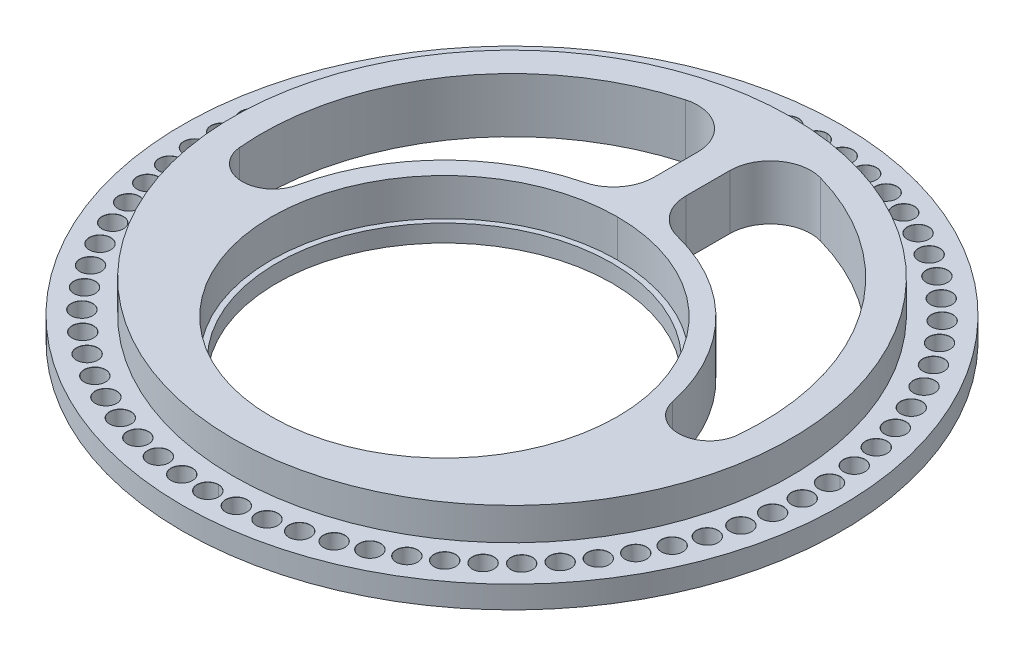
SolidWorks part; units mm, degrees
material "6061-T6 (SS)"
ref_plane "X-Y Datum" through (0, 0, 0) normal (0, 0, 1) x (1, 0, 0)
ref_plane "X-Z Datum" through (0, 0, 0) normal (0, 1, 0) x (1, 0, 0)
ref_plane "Y-Z Datum" through (0, 0, 0) normal (1, 0, 0) x (0, 0, -1)
sketch "Sketch1" plane through (0, 0, 0) normal (0, 1, 0) x (1, 0, 0)
  line L0 (0, 0) -> (0, -12.7) construction
  line L1 (0, -43.0151) -> (0, 43.0151) construction
  line L2 (0, 52.3875) -> (0, 61.9125) construction
  circle A0 centre (0, -12.7) radius 30.988
  circle A1 centre (0, 0) radius 52.3875 construction
  circle A2 centre (0, 0) radius 61.9125
  circle A3 centre (0, 0) radius 57.15 construction
  point P12 (0, 57.15)
  dimension "D2" = 61.976
  dimension "D3" = 104.775
  dimension "D4" = 123.825
  dimension "D5" = 114.3
  dimension "D1" = 12.7
extrude "Slotted-Body Extrude" add sketch "Sketch1" along normal blind 4.191
sketch "Sketch5" plane through (0, 4.191, 0) normal (0, 1, 0) x (1, 0, 0)
  circle A0 centre (0, 0) radius 52.3875 construction
  circle A1 centre (0, 0) radius 52.3875
extrude "Boss-Extrude3" add sketch "Sketch5" along normal blind 6.08
sketch "Sketch6" plane through (0, 0, 0) normal (0, -1, 0) x (1, 0, 0)
  line L0 (0, -79.2756) -> (0, 0) construction
  line L2 (3.014, -37.9067) -> (3.014, -29.6741)
  line L4 (-3.014, -37.9067) -> (-3.014, -29.6741)
  circle A0 centre (0, 12.7) radius 30.988 construction
  circle A1 centre (0, 12.7) radius 30.988 construction
  circle A2 centre (0, 12.7) radius 32.512
  arc A9 (-35.2562, 5.0907) -> (-8.7792, -22.2832) centre (0, 12.7) ccw
  arc A10 (-46.783, 4.406) -> (-12.6921, -45.2435) centre (0, 0) ccw
  arc A11 (-46.783, 4.406) -> (-35.2562, 5.0907) centre (-40.9667, 3.8583) cw
  arc A19 (-3.014, -29.6741) -> (-8.7792, -22.2832) centre (-10.634, -29.6741) ccw
  arc A20 (-3.014, -37.9067) -> (-12.6921, -45.2435) centre (-10.634, -37.9067) cw
  circle A21 centre (0, 0) radius 61.9125 construction
  arc A27 (46.783, 4.406) -> (35.2562, 5.0907) centre (40.9667, 3.8583) ccw
  arc A28 (46.783, 4.406) -> (12.6921, -45.2435) centre (0, 0) cw
  arc A29 (3.014, -37.9067) -> (12.6921, -45.2435) centre (10.634, -37.9067) ccw
  arc A30 (3.014, -29.6741) -> (8.7792, -22.2832) centre (10.634, -29.6741) cw
  arc A31 (35.2562, 5.0907) -> (8.7792, -22.2832) centre (0, 12.7) cw
  point P30 (0, 0)
  point P31 (-3.014, -23.2419)
  point P32 (0, 0)
  point P36 (-3.014, -46.8932)
  dimension "D1" = 65.024
  dimension "D2" = 7.62
  dimension "D3" = 5.842
  dimension "D4" = 46.99
  dimension "D5" = 7.62
  dimension "D6" = 36.068
  dimension "D8" = 8.2326
extrude "Cut-Extrude5" cut sketch "Sketch6" against normal through all
sketch "Sketch8" plane through (0, 0, 0) normal (0, -1, 0) x (1, 0, 0)
  circle A0 centre (0, 12.7) radius 32.512 construction
  circle A1 centre (0, 12.7) radius 32.512
  circle A2 centre (0, 12.7) radius 31.496
  dimension "D1" = 62.992
extrude "Boss-Extrude4" add sketch "Sketch8" against normal blind 3.255 separate body
hole_wizard "Ø4.0mm Dowel Hole2" positions "Sketch9" profile "Sketch10" hole size "Ø4.0" standard "ANSI Metric" end condition through all
sketch "Sketch9" plane through (0, 4.191, 0) normal (0, 1, 0) x (1, 0, 0)
  point P0 (0, 57.15)
sketch "Sketch10" plane through (0, 4.191, -57.15) normal (1, 0, 0) x (0, 0, 1)
  line L0 (0, 0) -> (0, 4.191)
  line L1 (0, 4.191) -> (2, 4.191)
  line L2 (2, 4.191) -> (2, 0.025)
  line L3 (2, 0.025) -> (2.025, 0)
  line L5 (2.025, 0) -> (0, 0)
  line L6 (-2, 0.025) -> (-2.025, 0) construction
  line L11 (0, -6.35) -> (0, 107.95) construction
  dimension "Thru Hole Dia." = 4
  dimension "Thru Hole Depth" = 4.191
  dimension "Near C'Sink Dia." = 4.05
  dimension "Near C'Sink Angle" = 90
pattern_circular "CirPattern1" count 70 over 360 about axis through (0, 0, 0) along (0, 1, 0) of "Ø4.0mm Dowel Hole2"
ref_point "Point1"
ref_plane "Plane1" through (0, 0, 0) normal (1, 0, 0) x (0, 0, -1)
split line "Split Line1"
ref_point "Point2"
ref_point "Point3"
ref_point "Point4"
ref_point "Point5"
split line "Split Line2"
split line "Split Line3"
ref_plane "Plane2" through (-57.0925, 0, 0) normal (-1, 0, 0) x (0, 0, 1)
ref_plane "Plane3" through (57.0925, 0, 0) normal (-1, 0, 0) x (0, 0, 1)
split line "Split Line4"
split line "Split Line5"
